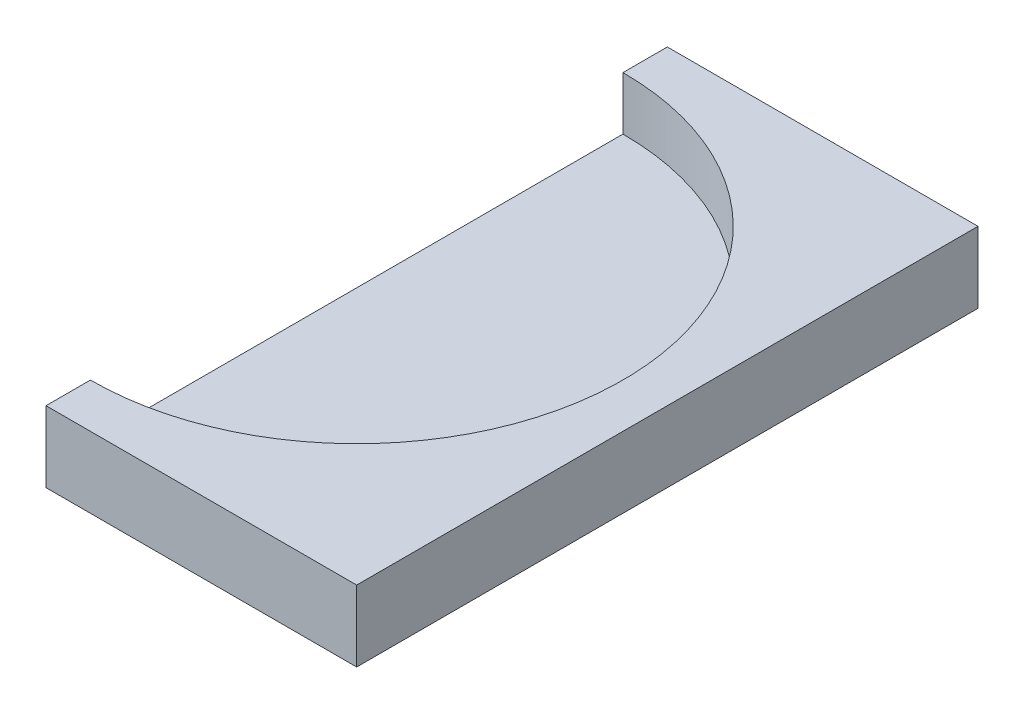
SolidWorks part; units mm, degrees
ref_plane "Спереди" through (0, 0, 0) normal (0, 0, 1) x (1, 0, 0)
ref_plane "Сверху" through (0, 0, 0) normal (0, 1, 0) x (1, 0, 0)
ref_plane "Справа" through (0, 0, 0) normal (1, 0, 0) x (0, 0, -1)
other "Configuration Table"
sketch "Эскиз1" plane through (0, 0, 0) normal (0, 1, 0) x (1, 0, 0)
  line L1 (-17.5, -35) -> (17.5, -35)
  line L2 (-17.5, -35) -> (-17.5, 35)
  line L3 (-17.5, 35) -> (17.5, 35)
  line L4 (17.5, -35) -> (17.5, 35)
  line L5 (-17.5, -35) -> (17.5, 35) construction
  line L6 (-17.5, 35) -> (17.5, -35) construction
  point P0 (0, 0)
extrude "Бобышка-Вытянуть1" add sketch "Эскиз1" along normal blind 8
sketch "Эскиз2" plane through (0, 8, 0) normal (0, 1, 0) x (1, 0, 0)
  line L1 (-17.5, 35) -> (-17.5, -35) construction
  circle A2 centre (-17.5, 0) radius 30
extrude "Вырез-Вытянуть1" cut sketch "Эскиз2" against normal blind 6
